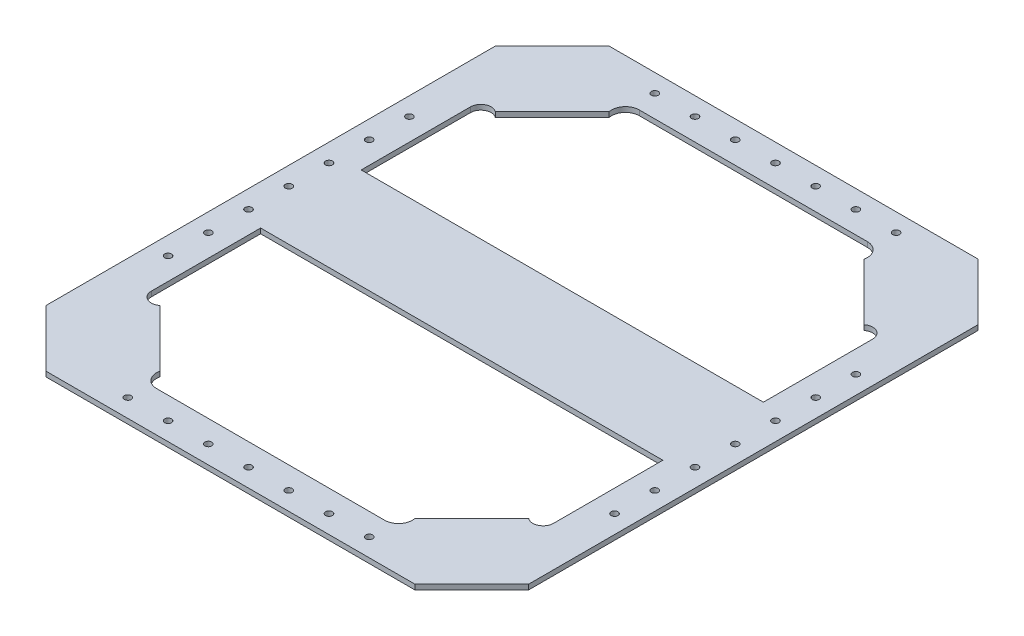
SolidWorks part; units mm, degrees
ref_plane "Front Plane" through (0, 0, 0) normal (0, 0, 1) x (1, 0, 0)
ref_plane "Top Plane" through (0, 0, 0) normal (0, 1, 0) x (1, 0, 0)
ref_plane "Right Plane" through (0, 0, 0) normal (1, 0, 0) x (0, 0, -1)
sketch "Sketch1" plane through (0, 0, 0) normal (0, 1, 0) x (1, 0, 0)
  line L0 (-152.4, 119.0596) -> (-116.479, 154.9807)
  line L1 (-116.479, 154.9807) -> (116.479, 154.9807)
  line L2 (-152.4, 119.0596) -> (-152.4, -164.6983)
  line L3 (152.4, 119.0596) -> (152.4, -164.6983)
  line L4 (152.4, 119.0596) -> (116.479, 154.9807)
  line L5 (0, 154.9807) -> (0, -200.6193) construction
  line L6 (-152.4, -22.8193) -> (152.4, -22.8193) construction
  line L7 (152.4, -164.6983) -> (116.479, -200.6193)
  line L8 (-116.479, -200.6193) -> (116.479, -200.6193)
  line L9 (-152.4, -164.6983) -> (-116.479, -200.6193)
  point P9 (0, -22.8193)
  point P11 (0, -22.8193)
  dimension "D1" = 355.6
  dimension "D3" = 50.8
  dimension "D4" = 135
extrude "Boss-Extrude1" add sketch "Sketch1" along normal blind 3.175
sketch "Sketch2" plane through (0, 3.175, 0) normal (0, 1, 0) x (1, 0, 0)
  line L0 (-152.4, -22.8193) -> (199.0625, -22.8193) construction
  line L1 (-152.4, 119.0596) -> (-152.4, -164.6983) construction
  line L2 (-91.079, 129.5807) -> (91.079, 129.5807)
  line L4 (82.443, 8.9307) -> (-74.315, 8.9307)
  line L6 (-116.479, 154.9807) -> (-91.079, 129.5807) construction
  line L7 (116.479, 154.9807) -> (91.079, 129.5807) construction
  line L8 (116.479, 154.9807) -> (-116.479, 154.9807) construction
  line L9 (-74.315, 8.9307) -> (-127, 8.9307)
  line L10 (-127, 8.9307) -> (-127, 93.6596)
  line L11 (-127, 93.6596) -> (-91.079, 129.5807)
  line L12 (82.443, 8.9307) -> (127, 8.9307)
  line L13 (127, 8.9307) -> (127, 93.6596)
  line L14 (127, 93.6596) -> (91.079, 129.5807)
  line L16 (127, -139.2983) -> (91.079, -175.2193)
  line L17 (127, -54.5693) -> (127, -139.2983)
  line L18 (82.443, -54.5693) -> (127, -54.5693)
  line L19 (-127, -139.2983) -> (-91.079, -175.2193)
  line L20 (-127, -54.5693) -> (-127, -139.2983)
  line L21 (-74.315, -54.5693) -> (-127, -54.5693)
  line L23 (82.443, -54.5693) -> (-74.315, -54.5693)
  line L25 (-91.079, -175.2193) -> (91.079, -175.2193)
  dimension "D1" = 135
  dimension "D2" = 135
  dimension "D3" = 25.4
  dimension "D4" = 90
  dimension "D5" = 90
  dimension "D6" = 50.8
  dimension "D7" = 50.8
  dimension "D8" = 31.75
  dimension "D9" = 25.4
extrude "Cut-Extrude1" cut sketch "Sketch2" against normal through all
sketch "Sketch4" plane through (0, 3.175, 0) normal (0, 1, 0) x (1, 0, 0)
  line L0 (-152.4, -22.8193) -> (171.6111, -22.8193) construction
  line L1 (-152.4, 119.0596) -> (-152.4, -164.6983) construction
  line L2 (116.479, 154.9807) -> (-116.479, 154.9807) construction
  line L4 (152.4, -164.6983) -> (152.4, 119.0596) construction
  circle A0 centre (0, 143.5507) radius 2.159
  circle A1 centre (-50.8, 143.5507) radius 2.159
  circle A2 centre (50.8, 143.5507) radius 2.159
  circle A3 centre (-25.4, 143.5507) radius 2.159
  circle A4 centre (25.4, 143.5507) radius 2.159
  circle A5 centre (-140.97, -22.8193) radius 2.159
  circle A6 centre (-140.97, 2.5807) radius 2.159
  circle A7 centre (-140.97, 27.9807) radius 2.159
  circle A8 centre (140.97, -22.8193) radius 2.159
  circle A9 centre (140.97, 2.5807) radius 2.159
  circle A10 centre (140.97, 27.9807) radius 2.159
  circle A11 centre (140.97, -73.6193) radius 2.159
  circle A12 centre (140.97, -48.2193) radius 2.159
  circle A13 centre (-140.97, -73.6193) radius 2.159
  circle A14 centre (-140.97, -48.2193) radius 2.159
  circle A15 centre (25.4, -189.1893) radius 2.159
  circle A16 centre (-25.4, -189.1893) radius 2.159
  circle A17 centre (50.8, -189.1893) radius 2.159
  circle A18 centre (-50.8, -189.1893) radius 2.159
  circle A19 centre (0, -189.1893) radius 2.159
  circle A20 centre (-76.2, 143.5507) radius 2.159
  circle A21 centre (76.2, 143.5507) radius 2.159
  circle A22 centre (-140.97, 53.3807) radius 2.159
  circle A23 centre (140.97, 53.3807) radius 2.159
  circle A24 centre (140.97, -99.0193) radius 2.159
  circle A25 centre (76.2, -189.1893) radius 2.159
  circle A26 centre (-76.2, -189.1893) radius 2.159
  circle A27 centre (-140.97, -99.0193) radius 2.159
  point P48 (0, 154.9807)
  point P56 (0, 0)
  point P57 (0, 0)
  dimension "D1" = 4.318
  dimension "D2" = 4.318
  dimension "D3" = 4.318
  dimension "D4" = 4.318
  dimension "D5" = 4.318
  dimension "D6" = 4.318
  dimension "D7" = 4.318
  dimension "D8" = 4.318
  dimension "D9" = 4.318
  dimension "D10" = 4.318
  dimension "D11" = 4.318
  dimension "D23" = 4.318
  dimension "D24" = 4.318
  dimension "D27" = 4.318
  dimension "D28" = 4.318
  dimension "D12" = 25.4
  dimension "D13" = 25.4
  dimension "D14" = 25.4
  dimension "D15" = 25.4
  dimension "D16" = 25.4
  dimension "D17" = 25.4
  dimension "D18" = 25.4
  dimension "D19" = 25.4
  dimension "D20" = 11.43
  dimension "D21" = 11.43
  dimension "D22" = 11.43
  dimension "D25" = 25.4
  dimension "D26" = 25.4
  dimension "D29" = 25.4
  dimension "D30" = 25.4
sketch "Sketch5" plane through (0, 3.175, 0) normal (0, 1, 0) x (1, 0, 0)
  line L0 (-116.479, 83.1386) -> (-80.558, 119.0596)
  line L1 (0, 129.5807) -> (0, -138.0704) construction
  line L3 (-152.4, 119.0596) -> (-152.4, 65.2582)
  line L4 (-127, 93.6596) -> (-127, 8.9307) construction
  line L5 (91.079, 129.5807) -> (-91.079, 129.5807) construction
  line L6 (-116.479, 154.9807) -> (-59.329, 154.9807)
  line L7 (116.479, 154.9807) -> (-116.479, 154.9807) construction
  line L8 (-59.329, 154.9807) -> (-59.329, 129.5807)
  line L9 (-152.4, 119.0596) -> (-116.479, 154.9807)
  line L10 (-152.4, 119.0596) -> (-152.4, -164.6983) construction
  line L12 (-152.4, 65.2582) -> (-127, 65.2582)
  line L13 (-59.329, 129.5807) -> (-72.029, 129.5807)
  line L14 (127, 65.2582) -> (127, 77.9582)
  line L15 (152.4, -22.8193) -> (-208.2375, -22.8193) construction
  line L16 (152.4, -164.6983) -> (152.4, 119.0596) construction
  line L17 (59.329, 129.5807) -> (72.029, 129.5807)
  line L18 (-127, 65.2582) -> (-127, 77.9582)
  line L19 (152.4, 65.2582) -> (127, 65.2582)
  line L20 (152.4, 119.0596) -> (116.479, 154.9807)
  line L21 (59.329, 154.9807) -> (59.329, 129.5807)
  line L22 (116.479, 154.9807) -> (59.329, 154.9807)
  line L24 (152.4, 119.0596) -> (152.4, 65.2582)
  line L25 (116.479, 83.1386) -> (80.558, 119.0596)
  line L26 (116.479, -128.7773) -> (80.558, -164.6983)
  line L27 (152.4, -164.6983) -> (152.4, -110.8969)
  line L28 (116.479, -200.6193) -> (59.329, -200.6193)
  line L29 (59.329, -200.6193) -> (59.329, -175.2193)
  line L30 (152.4, -164.6983) -> (116.479, -200.6193)
  line L31 (152.4, -110.8969) -> (127, -110.8969)
  line L32 (-127, -110.8969) -> (-127, -123.5969)
  line L33 (59.329, -175.2193) -> (72.029, -175.2193)
  line L34 (127, -110.8969) -> (127, -123.5969)
  line L35 (-59.329, -175.2193) -> (-72.029, -175.2193)
  line L36 (-152.4, -110.8969) -> (-127, -110.8969)
  line L37 (-152.4, -164.6983) -> (-116.479, -200.6193)
  line L38 (-59.329, -200.6193) -> (-59.329, -175.2193)
  line L39 (-116.479, -200.6193) -> (-59.329, -200.6193)
  line L40 (-152.4, -164.6983) -> (-152.4, -110.8969)
  line L41 (-116.479, -128.7773) -> (-80.558, -164.6983)
  arc A0 (-72.029, 129.5807) -> (-80.558, 119.0596) centre (-72.029, 120.8631) ccw
  arc A1 (-127, 77.9582) -> (-116.479, 83.1386) centre (-120.4641, 77.9582) cw
  arc A2 (127, 77.9582) -> (116.479, 83.1386) centre (120.4641, 77.9582) ccw
  arc A3 (72.029, 129.5807) -> (80.558, 119.0596) centre (72.029, 120.8631) cw
  arc A4 (72.029, -175.2193) -> (80.558, -164.6983) centre (72.029, -166.5018) ccw
  arc A5 (127, -123.5969) -> (116.479, -128.7773) centre (120.4641, -123.5969) cw
  arc A6 (-127, -123.5969) -> (-116.479, -128.7773) centre (-120.4641, -123.5969) ccw
  arc A7 (-72.029, -175.2193) -> (-80.558, -164.6983) centre (-72.029, -166.5018) cw
  dimension "D3" = 12.7
  dimension "D1" = 50.8
  dimension "D2" = 50.8
  dimension "D4" = 12.7
  dimension "D5" = 57.15
  dimension "D6" = 53.8014
extrude "Boss-Extrude2" add sketch "Sketch5" against normal blind 3.175
extrude "Cut-Extrude2" cut sketch "Sketch4" against normal through all
